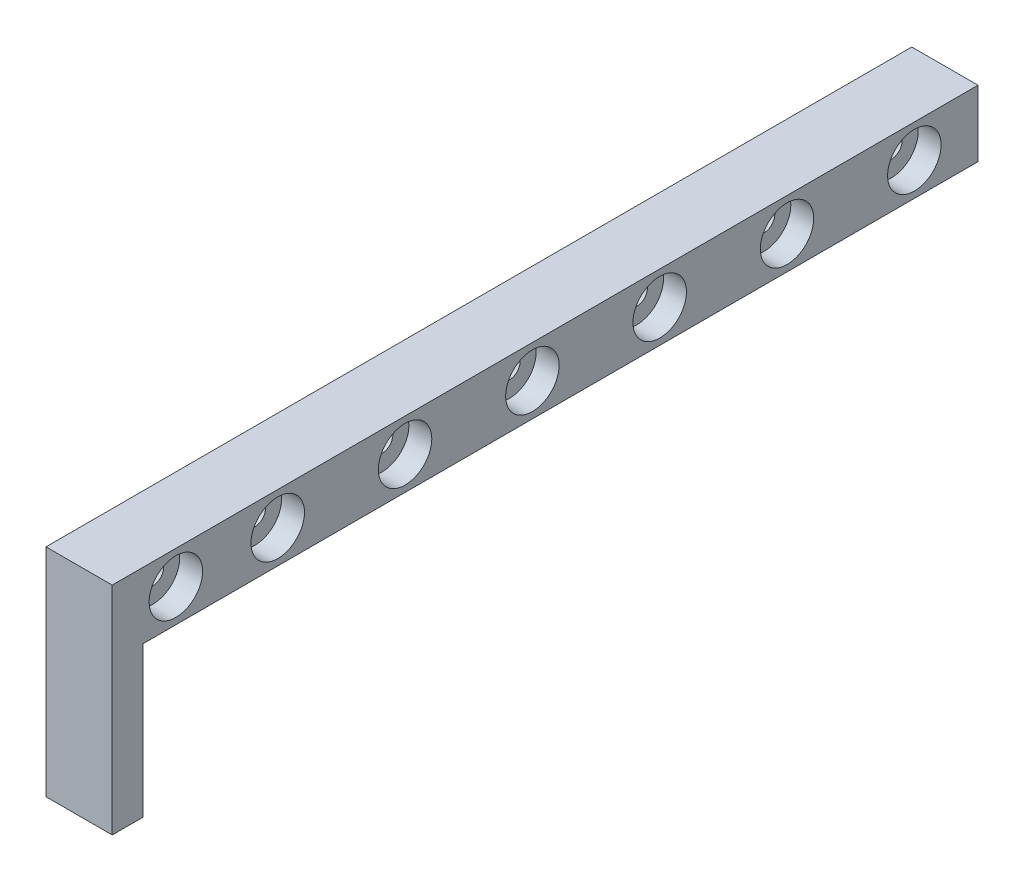
SolidWorks part; units mm, degrees
ref_plane "Front Plane" through (0, 0, 0) normal (0, 0, 1) x (1, 0, 0)
ref_plane "Top Plane" through (0, 0, 0) normal (0, 1, 0) x (1, 0, 0)
ref_plane "Right Plane" through (0, 0, 0) normal (1, 0, 0) x (0, 0, -1)
sketch "Sketch1" plane through (0, 0, 0) normal (0, 0, 1) x (1, 0, 0)
  line L0 (-6.5, -6.5) -> (6.5, -6.5)
  line L1 (6.5, -6.5) -> (6.5, 6.5)
  line L2 (6.5, 6.5) -> (-6.5, 6.5)
  line L3 (-6.5, 6.5) -> (-6.5, -6.5)
extrude "Boss-Extrude1" add sketch "Sketch1" along normal mid plane 170
ref_plane "Plane1" through (0, 0, 82) normal (0, 0, 1) x (1, 0, 0)
sketch "Sketch2" plane through (0, 0, 82) normal (0, 0, 1) x (1, 0, 0)
  line L0 (-6.5, -36) -> (6.5, -36)
  line L1 (6.5, -36) -> (6.5, -5.5)
  line L2 (6.5, -5.5) -> (-6.5, -5.5)
  line L3 (-6.5, -5.5) -> (-6.5, -36)
extrude "Boss-Extrude2" add sketch "Sketch2" along normal mid plane 6
sketch "Sketch3" plane through (0, 0, 0) normal (1, 0, 0) x (0, 0, -1)
  circle A0 centre (72.5, 0) radius 2.1
  circle A1 centre (47.5, 0) radius 2.1
  circle A2 centre (22.5, 0) radius 2.1
  circle A3 centre (-2.5, 0) radius 2.1
  circle A4 centre (-27.5, 0) radius 2.1
  circle A5 centre (-52.5, 0) radius 2.1
  circle A6 centre (-72.5, 0) radius 2.1
extrude "Cut-Extrude1" cut sketch "Sketch3" against normal mid plane 23
ref_plane "Plane2" through (6.5, 0, 0) normal (1, 0, 0) x (0, 0, -1)
sketch "Sketch4" plane through (6.5, 0, 0) normal (1, 0, 0) x (0, 0, -1)
  circle A0 centre (72.5, 0) radius 5.25
  circle A1 centre (47.5, 0) radius 5.25
  circle A2 centre (22.5, 0) radius 5.25
  circle A3 centre (-2.5, 0) radius 5.25
  circle A4 centre (-27.5, 0) radius 5.25
  circle A5 centre (-52.5, 0) radius 5.25
  circle A6 centre (-72.5, 0) radius 5.25
extrude "Cut-Extrude2" cut sketch "Sketch4" against normal mid plane 9
